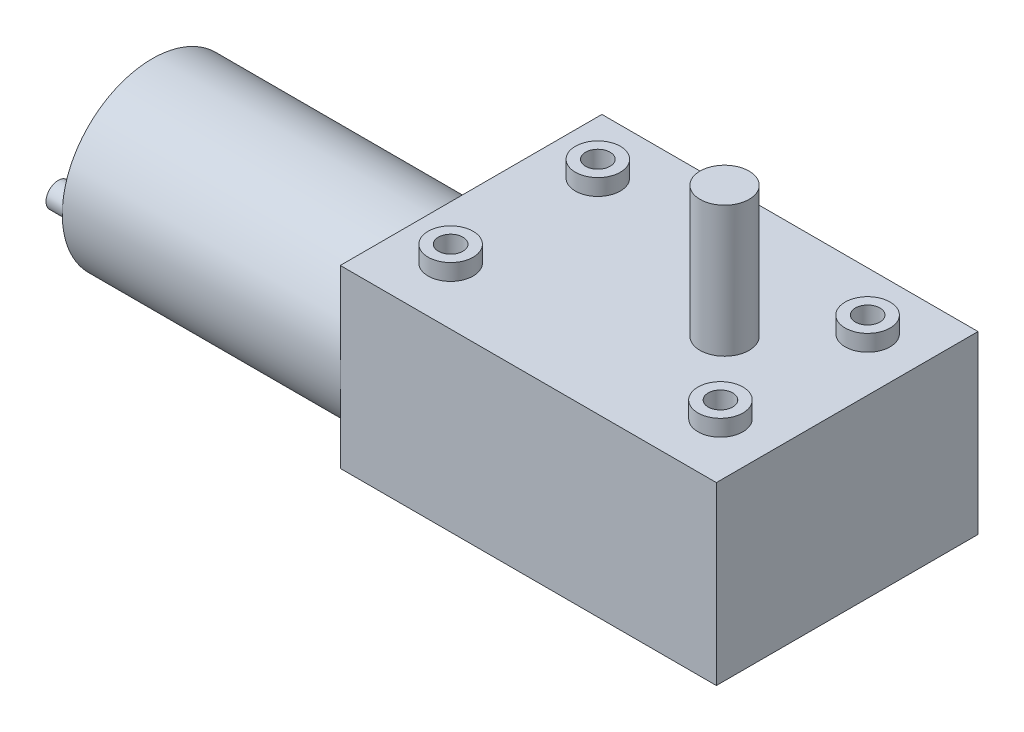
SolidWorks part; units mm, degrees
ref_plane "Front Plane" through (0, 0, 0) normal (0, 0, 1) x (1, 0, 0)
ref_plane "Top Plane" through (0, 0, 0) normal (0, 1, 0) x (1, 0, 0)
ref_plane "Right Plane" through (0, 0, 0) normal (1, 0, 0) x (0, 0, -1)
sketch "Sketch1" plane through (0, 0, 0) normal (0, 1, 0) x (1, 0, 0)
  line L1 (-23, -16) -> (23, -16)
  line L2 (-23, -16) -> (-23, 16)
  line L3 (-23, 16) -> (23, 16)
  line L4 (23, -16) -> (23, 16)
  line L5 (-23, -16) -> (23, 16) construction
  line L6 (-23, 16) -> (23, -16) construction
  point P0 (0, 0)
  dimension "D1" = 32
  dimension "D2" = 46
extrude "Boss-Extrude1" add sketch "Sketch1" along normal blind 21.5
sketch "Sketch2" plane through (0, 21.5, 0) normal (0, 1, 0) x (1, 0, 0)
  line L1 (-23, 16) -> (-23, -16) construction
  line L3 (-11.825, 0) -> (11.825, 0) construction
  line L4 (0, -11.825) -> (0, 11.825) construction
  circle A0 centre (-16.5, 9) radius 1.5
  circle A1 centre (-16.5, -9) radius 1.5
  circle A2 centre (16.5, -9) radius 1.5
  circle A3 centre (16.5, 9) radius 1.5
  circle A4 centre (-16.5, 9) radius 2.75
  circle A5 centre (-16.5, -9) radius 2.75
  circle A6 centre (16.5, -9) radius 2.75
  circle A7 centre (16.5, 9) radius 2.75
  dimension "D3" = 3
  dimension "D4" = 5.5
  dimension "D1" = 18
  dimension "D2" = 6.5
hole_wizard "Ø3.0mm Dowel Hole1" positions "3DSketch1" profile "Sketch3" hole size "Ø3.0" standard "ANSI Metric"
sketch3d "3DSketch1"
  point P0 (-16.5, 21.5, -9)
  point P3 (16.5, 21.5, -9)
  point P6 (16.5, 21.5, 9)
  point P9 (-16.5, 21.5, 9)
sketch "Sketch3" plane through (-16.5, 21.5, -9) normal (1, 0, 0) x (0, 0, 1)
  line L0 (0, 0) -> (0, 6.4913)
  line L1 (0, 6.4913) -> (1.5, 5.59)
  line L2 (1.5, 5.59) -> (1.5, 0)
  line L5 (1.5, 0) -> (0, 0)
  line L10 (0, 6.4913) -> (-1.5, 5.59) construction
  line L11 (0, -6.35) -> (0, 107.95) construction
  dimension "Hole Dia." = 3
  dimension "Hole Depth" = 5.59
  dimension "Drill Angle" = 118
extrude "Boss-Extrude2" add sketch "Sketch2" along normal blind 2
sketch "Sketch4" plane through (0, 21.5, 0) normal (0, 1, 0) x (1, 0, 0)
  line L0 (23, -16) -> (23, 16) construction
  circle A0 centre (8, 0) radius 3
  dimension "D1" = 15
extrude "Boss-Extrude3" add sketch "Sketch4" along normal blind 16
sketch "Sketch5" plane through (-23, 0, 0) normal (-1, 0, 0) x (0, 0, 1)
  line L0 (16, 21.5) -> (16, 0) construction
  line L1 (-16, 21.5) -> (16, 21.5) construction
  circle A1 centre (5, 9.9) radius 11
  dimension "D1" = 22
  dimension "D2" = 11.6
extrude "Boss-Extrude4" add sketch "Sketch5" along normal blind 34
sketch "Sketch6" plane through (-57, 0, 0) normal (-1, 0, 0) x (0, 0, 1)
  circle A0 centre (14.4931, 10.2623) radius 1.5
  circle A1 centre (-4.4947, 10.2162) radius 1.5
  circle A2 centre (5, 9.9) radius 11 construction
extrude "Boss-Extrude5" add sketch "Sketch6" along normal blind 2
